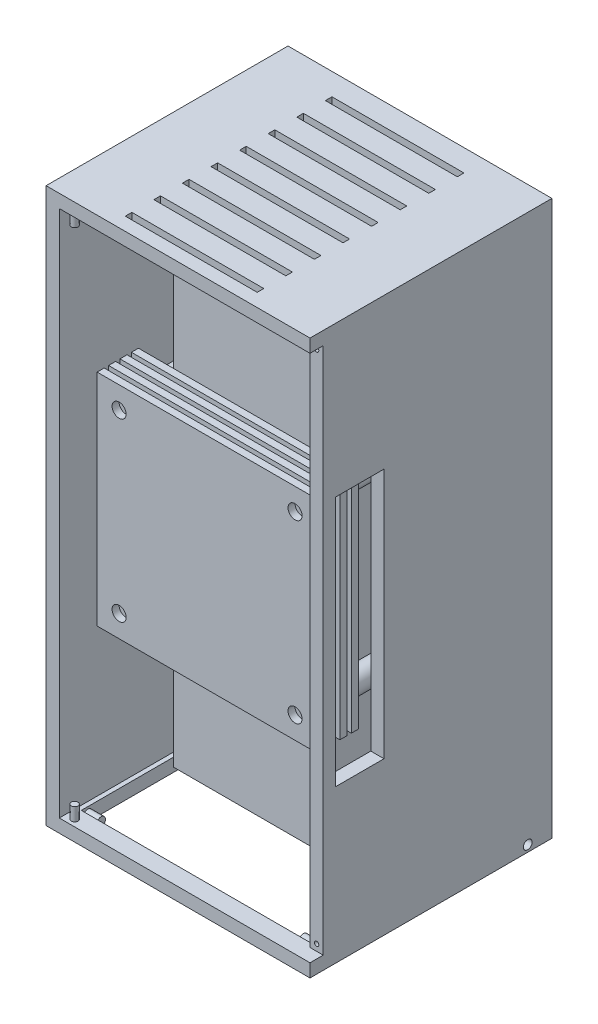
SolidWorks part; units mm, degrees
ref_plane "前视基准面" through (0, 0, 0) normal (0, 0, 1) x (1, 0, 0)
ref_plane "上视基准面" through (0, 0, 0) normal (0, 1, 0) x (1, 0, 0)
ref_plane "右视基准面" through (0, 0, 0) normal (1, 0, 0) x (0, 0, -1)
sketch "草图1" plane through (0, 0, 0) normal (0, 0, 1) x (1, 0, 0)
  line L1 (0, 0) -> (50, 0)
  line L2 (0, 0) -> (0, -50)
  line L3 (0, -50) -> (50, -50)
  line L4 (50, 0) -> (50, -50)
  dimension "D1" = 50
  dimension "D2" = 50
extrude "凸台-拉伸1" add sketch "草图1" along normal blind 1.6
ref_plane "基准面5" through (0, 0, -1) normal (0, 0, -1) x (-1, 0, 0)
sketch "草图4" plane through (0, 0, -1) normal (0, 0, -1) x (-1, 0, 0)
  line L0 (-50, -50) -> (-50, 0) construction
  line L1 (-50, -50) -> (0, -50)
  line L2 (-50, -50) -> (-50, 0)
  line L3 (-50, 0) -> (0, 0)
  line L4 (0, -50) -> (0, 0)
extrude "凸台-拉伸3" add sketch "草图4" along normal blind 1.6 separate body
ref_plane "基准面6" through (0, 0, -3.6) normal (0, 0, -1) x (-1, 0, 0)
sketch "草图5" plane through (0, 0, -3.6) normal (0, 0, -1) x (-1, 0, 0)
  line L1 (0, 0) -> (-50, 0)
  line L2 (0, 0) -> (0, -50)
  line L3 (0, -50) -> (-50, -50)
  line L4 (-50, 0) -> (-50, -50)
extrude "凸台-拉伸4" add sketch "草图5" along normal blind 1.6 separate body
ref_plane "基准面7" through (0, 0, -6.2) normal (0, 0, -1) x (-1, 0, 0)
sketch "草图6" plane through (0, 0, -6.2) normal (0, 0, -1) x (-1, 0, 0)
  line L0 (-50, 0) -> (-50, -50) construction
  line L1 (0, 0) -> (-50, 0)
  line L2 (0, 0) -> (0, -50)
  line L3 (0, -50) -> (-50, -50)
  line L4 (-50, 0) -> (-50, -50)
extrude "凸台-拉伸5" add sketch "草图6" along normal blind 1.6 separate body
ref_plane "基准面8" through (0, 0, -7.8) normal (0, 0, -1) x (-1, 0, 0)
sketch "草图9" plane through (0, 0, -7.8) normal (0, 0, -1) x (-1, 0, 0)
  line L0 (-50, 0) -> (-50, -50) construction
  line L1 (-42, 28.5) -> (-8, 28.5)
  line L2 (-42, 28.5) -> (-42, -78.5)
  line L3 (-42, -78.5) -> (-8, -78.5)
  line L4 (-8, 28.5) -> (-8, -78.5)
  line L5 (0, -50) -> (0, 0) construction
  line L6 (0, 0) -> (-50, 0) construction
  line L7 (-50, -50) -> (0, -50) construction
  dimension "D1" = 8
  dimension "D2" = 8
  dimension "D3" = 28.5
  dimension "D4" = 28.5
extrude "凸台-拉伸6" add sketch "草图9" along normal blind 34 contours L2 L1 L4 L3
fillet "圆角12" radius 3 1 edges at (8, -25, -41.8)
fillet "圆角13" radius 3 1 edges at (42, -25, -41.8)
sketch "草图10" plane through (0, 0, 1.6) normal (0, 0, 1) x (1, 0, 0)
  line L0 (0, 0) -> (0, -50) construction
  line L1 (50, 0) -> (0, 0) construction
  line L2 (50, -50) -> (50, 0) construction
  line L3 (0, -50) -> (50, -50) construction
  circle A0 centre (5, -5) radius 1.6
  circle A1 centre (45, -5) radius 1.6
  circle A2 centre (5, -45) radius 1.6
  circle A3 centre (45, -45) radius 1.6
  dimension "D7" = 3.2
  dimension "D8" = 3.2
  dimension "D9" = 3.2
  dimension "D10" = 3.2
  dimension "D1" = 5
  dimension "D2" = 5
  dimension "D3" = 5
  dimension "D4" = 5
  dimension "D5" = 5
  dimension "D6" = 5
  dimension "D11" = 5
  dimension "D12" = 5
extrude "切除-拉伸1" cut sketch "草图10" against normal blind 10 contours A2 | A0 | A3 | A1
ref_plane "基准面14" through (0, 0, -20.1) normal (0, 0, 1) x (1, 0, 0)
ref_plane "基准面15" through (0, 0, 1.6) normal (0, 0, 1) x (1, 0, 0)
ref_plane "基准面16" through (0, 0, -43.8) normal (0, 0, -1) x (-1, 0, 0)
sketch "草图17" plane through (0, 0, -43.8) normal (0, 0, -1) x (-1, 0, 0)
  line L0 (-39, 28.5) -> (-11, 28.5) construction
  line L1 (-52, 34.5) -> (2, 34.5)
  line L2 (-52, 34.5) -> (-52, -85.5)
  line L3 (-52, -85.5) -> (2, -85.5)
  line L4 (2, 34.5) -> (2, -85.5)
  line L5 (0, -50) -> (0, 0) construction
  dimension "D1" = 120
  dimension "D2" = 6
  dimension "D3" = 54
  dimension "D4" = 2
extrude "凸台-拉伸8" add sketch "草图17" along normal blind 3 separate body
ref_plane "基准面17" through (0, -78.5, 0) normal (0, -1, 0) x (-1, 0, 0)
sketch "草图18" plane through (0, -78.5, 0) normal (0, -1, 0) x (-1, 0, 0)
  line L0 (-8, 38.8) -> (-8, 7.8) construction
  circle A0 centre (-25.0675, 24.3887) radius 15
  dimension "D1" = 30
  dimension "D2" = 17.0675
extrude "凸台-拉伸10" add sketch "草图18" along normal blind 1
ref_plane "基准面18" through (0, -79.5, 0) normal (0, -1, 0) x (-1, 0, 0)
sketch "草图19" plane through (0, -79.5, 0) normal (0, -1, 0) x (-1, 0, 0)
  line L0 (-39, 41.8) -> (-11, 41.8) construction
  circle A0 centre (-25.6075, 24.3) radius 4.5304
  dimension "D1" = 9.0607
  dimension "D2" = 17.5
extrude "凸台-拉伸11" add sketch "草图19" along normal blind 3
sketch "草图22" plane through (0, 0, -7.8) normal (0, 0, -1) x (-1, 0, 0)
  circle A0 centre (-45, -45) radius 2.5
  circle A1 centre (-45, -5) radius 2
  circle A2 centre (-5, -45) radius 2.5
  circle A3 centre (-5, -5) radius 2.5
extrude "凸台-拉伸12" add sketch "草图22" along normal blind 37
ref_plane "基准面19" through (0, 0, -7.8) normal (0, 0, 1) x (1, 0, 0)
sketch "草图23" plane through (0, 0, -7.8) normal (0, 0, 1) x (1, 0, 0)
  circle A0 centre (45, -45) radius 1.6
  circle A1 centre (45, -5) radius 1.6
  circle A2 centre (5, -5) radius 1.6
  circle A3 centre (5, -45) radius 1.6
extrude "切除-拉伸2" cut sketch "草图23" against normal blind 3
ref_plane "基准面21" through (0, 0, -46.8) normal (0, 0, -1) x (-1, 0, 0)
sketch "草图24" plane through (0, 0, -46.8) normal (0, 0, -1) x (-1, 0, 0)
  line L1 (-55, 37.5) -> (5, 37.5)
  line L2 (-55, 37.5) -> (-55, -88.5)
  line L3 (-55, -88.5) -> (5, -88.5)
  line L4 (5, 37.5) -> (5, -88.5)
  line L6 (2, -85.5) -> (2, 34.5) construction
  line L7 (-52, -85.5) -> (2, -85.5) construction
  line L9 (-52, 34.5) -> (2, 34.5)
  line L10 (-52, 34.5) -> (-52, -85.5)
  line L11 (-52, -85.5) -> (2, -85.5)
  line L12 (2, 34.5) -> (2, -85.5)
  dimension "D1" = 60
  dimension "D2" = 126
  dimension "D3" = 3
  dimension "D4" = 3
extrude "凸台-拉伸14" add sketch "草图24" against normal blind 55
ref_plane "基准面24" through (0, 0, 8.2) normal (0, 0, 1) x (1, 0, 0)
sketch "草图27" plane through (0, 0, 8.2) normal (0, 0, 1) x (1, 0, 0)
  line L0 (55, 37.5) -> (55, -88.5) construction
  line L1 (52, 34.5) -> (55, 34.5)
  line L2 (52, 34.5) -> (52, -85.5)
  line L3 (52, -85.5) -> (55, -85.5)
  line L4 (55, 34.5) -> (55, -85.5)
  line L5 (52, -85.5) -> (-2, -85.5) construction
  dimension "D1" = 0
ref_plane "基准面26" through (0, 0, 8.2) normal (0, 0, 1) x (1, 0, 0)
sketch "草图28" plane through (0, 0, 8.2) normal (0, 0, 1) x (1, 0, 0)
  line L0 (55, 37.5) -> (55, -88.5) construction
  line L1 (-2, -85.5) -> (55, -85.5)
  line L2 (-2, -85.5) -> (-2, 34.5)
  line L3 (-2, 34.5) -> (55, 34.5)
  line L4 (55, -85.5) -> (55, 34.5)
  dimension "D1" = 0
ref_plane "基准面31" through (0, -85.5, 0) normal (0, 1, 0) x (1, 0, 0)
sketch "草图29" plane through (0, -85.5, 0) normal (0, 1, 0) x (1, 0, 0)
  line L0 (-2, -8.2) -> (-2, 43.8) construction
  line L1 (-2, -8.2) -> (55, -8.2) construction
  circle A0 centre (0, -6.7) radius 0.75
  dimension "D1" = 1.5
  dimension "D2" = 2
  dimension "D3" = 1.5
ref_plane "基准面32" through (0, 34.5, 0) normal (0, -1, 0) x (-1, 0, 0)
sketch "草图30" plane through (0, 34.5, 0) normal (0, -1, 0) x (-1, 0, 0)
  line L0 (2, -8.2) -> (2, 43.8) construction
  line L1 (2, -8.2) -> (-55, -8.2) construction
  circle A0 centre (0, -6.7) radius 0.75
  dimension "D1" = 1.5
  dimension "D2" = 2
  dimension "D3" = 1.5
ref_plane "基准面33" through (0, 37.5, 0) normal (0, 1, 0) x (1, 0, 0)
sketch "草图31" plane through (0, 37.5, 0) normal (0, 1, 0) x (1, 0, 0)
  line L0 (-5, -8.2) -> (-5, 46.8) construction
  line L1 (10, 41.8) -> (40, 41.8)
  line L2 (10, 41.8) -> (10, 40.3)
  line L3 (10, 40.3) -> (40, 40.3)
  line L4 (40, 41.8) -> (40, 40.3)
  line L5 (10, 35.3) -> (40, 35.3)
  line L6 (10, 35.3) -> (10, 33.8)
  line L7 (10, 33.8) -> (40, 33.8)
  line L8 (40, 35.3) -> (40, 33.8)
  line L9 (10, 28.8) -> (40, 28.8)
  line L10 (10, 28.8) -> (10, 27.3)
  line L11 (10, 27.3) -> (40, 27.3)
  line L12 (40, 28.8) -> (40, 27.3)
  line L13 (10, 22.3) -> (40, 22.3)
  line L14 (10, 22.3) -> (10, 20.8)
  line L15 (10, 20.8) -> (40, 20.8)
  line L16 (40, 22.3) -> (40, 20.8)
  line L17 (10, 15.8) -> (40, 15.8)
  line L18 (10, 15.8) -> (10, 14.3)
  line L19 (10, 14.3) -> (40, 14.3)
  line L20 (40, 15.8) -> (40, 14.3)
  line L21 (10, 9.3) -> (40, 9.3)
  line L22 (10, 9.3) -> (10, 7.8)
  line L23 (10, 7.8) -> (40, 7.8)
  line L24 (40, 9.3) -> (40, 7.8)
  line L25 (10, 2.8) -> (40, 2.8)
  line L26 (10, 2.8) -> (10, 1.3)
  line L27 (10, 1.3) -> (40, 1.3)
  line L28 (40, 2.8) -> (40, 1.3)
  line L29 (10, -3.7) -> (40, -3.7)
  line L30 (10, -3.7) -> (10, -5.2)
  line L31 (10, -5.2) -> (40, -5.2)
  line L32 (40, -3.7) -> (40, -5.2)
  line L33 (-5, 46.8) -> (55, 46.8) construction
  dimension "D1" = 1.5
  dimension "D2" = 30
  dimension "D3" = 15
  dimension "D4" = 5
  dimension "D5" = 0
  dimension "D6" = 0
  dimension "D7" = 0
  dimension "D8" = 0
  dimension "D9" = 0
  dimension "D10" = 0
  dimension "D11" = 0
  dimension "D12" = 5
  dimension "D13" = 1.5
  dimension "D14" = 5
  dimension "D15" = 1.5
  dimension "D16" = 5
  dimension "D17" = 1.5
  dimension "D18" = 5
  dimension "D19" = 1.5
  dimension "D20" = 5
  dimension "D21" = 1.5
  dimension "D22" = 5
  dimension "D23" = 1.5
  dimension "D24" = 5
  dimension "D25" = 1.5
extrude "切除-拉伸4" cut sketch "草图31" against normal blind 4
ref_plane "基准面4" through (0, 0, -1) normal (0, 0, -1) x (-1, 0, 0)
ref_plane "基准面9" through (0, 0, 1.6) normal (0, 0, 1) x (1, 0, 0)
ref_plane "基准面34" through (0, 0, -43.8) normal (0, 0, 1) x (1, 0, 0)
sketch "草图32" plane through (0, 0, -43.8) normal (0, 0, 1) x (1, 0, 0)
  line L0 (-2, 34.5) -> (52, 34.5) construction
  line L1 (-2, -85.5) -> (-2, 34.5) construction
  line L2 (52, 34.5) -> (52, -85.5) construction
  line L3 (52, -85.5) -> (-2, -85.5) construction
  circle A0 centre (2, 30.5) radius 1
  circle A1 centre (48, 30.5) radius 1
  circle A2 centre (2, -81.5) radius 1
  circle A3 centre (48, -81.5) radius 1
  dimension "D1" = 2
  dimension "D4" = 2
  dimension "D7" = 2
  dimension "D8" = 4
  dimension "D11" = 2
  dimension "D2" = 4
  dimension "D3" = 4
  dimension "D5" = 4
  dimension "D6" = 4
  dimension "D9" = 4
  dimension "D10" = 4
  dimension "D12" = 4
extrude "切除-拉伸5" cut sketch "草图32" against normal blind 10
ref_plane "基准面35" through (0, -85.5, 0) normal (0, 1, 0) x (1, 0, 0)
sketch "草图33" plane through (0, -85.5, 0) normal (0, 1, 0) x (1, 0, 0)
  line L0 (-2, -8.2) -> (-2, 43.8) construction
  line L1 (52, -8.2) -> (-2, -8.2)
  line L2 (52, -8.2) -> (52, -5.2)
  line L3 (52, -5.2) -> (-2, -5.2)
  line L4 (-2, -8.2) -> (-2, -5.2)
  dimension "D1" = 3
extrude "凸台-拉伸15" add sketch "草图33" along normal blind 121
ref_plane "基准面36" through (0, -88.5, 0) normal (0, -1, 0) x (-1, 0, 0)
sketch "草图34" plane through (0, -88.5, 0) normal (0, -1, 0) x (-1, 0, 0)
  line L0 (-55, -8.2) -> (5, -8.2) construction
  line L1 (1, -4.2) -> (-51, -4.2)
  line L2 (1, -4.2) -> (1, 42.8)
  line L3 (1, 42.8) -> (-51, 42.8)
  line L4 (-51, -4.2) -> (-51, 42.8)
  line L5 (5, -8.2) -> (5, 46.8) construction
  line L6 (-55, -8.2) -> (-55, 46.8) construction
  line L7 (-55, 46.8) -> (5, 46.8) construction
  dimension "D1" = 4
  dimension "D2" = 4
  dimension "D3" = 4
  dimension "D4" = 4
extrude "切除-拉伸6" cut sketch "草图34" against normal blind 3
ref_plane "基准面39" through (0, -78.5, 0) normal (0, -1, 0) x (-1, 0, 0)
ref_plane "基准面40" through (55, 0, 0) normal (1, 0, 0) x (0, 0, -1)
sketch "草图36" plane through (55, 0, 0) normal (1, 0, 0) x (0, 0, -1)
  line L0 (-8.2, 37.5) -> (-8.2, -88.5) construction
  line L1 (-8.2, -88.5) -> (46.8, -88.5) construction
  circle A0 centre (-2.7, -87) radius 1
  dimension "D1" = 2
  dimension "D2" = 5.5
  dimension "D3" = 1.5
extrude "凸台-拉伸16" add sketch "草图36" against normal blind 58
ref_plane "基准面41" through (48, 0, 0) normal (-1, 0, 0) x (0, 0, 1)
sketch "草图37" plane through (48, 0, 0) normal (-1, 0, 0) x (0, 0, 1)
  line L0 (8.2, 37.5) -> (8.2, -88.5) construction
  line L1 (8.2, -88.5) -> (-46.8, -88.5) construction
  circle A0 centre (2.7, -87) radius 1
  dimension "D2" = 2
  dimension "D1" = 5.5
  dimension "D3" = 1.5
extrude "切除-拉伸8" cut sketch "草图37" along normal blind 46
sketch "草图38" plane through (55, 0, 0) normal (1, 0, 0) x (0, 0, -1)
  line L0 (46.8, 37.5) -> (46.8, -88.5) construction
  line L1 (-8.2, -88.5) -> (46.8, -88.5) construction
  circle A0 centre (41.3, -87) radius 1
  dimension "D1" = 2
  dimension "D2" = 5.5
  dimension "D3" = 1.5
extrude "切除-拉伸9" cut sketch "草图38" against normal blind 100
ref_plane "基准面42" through (55, 0, 0) normal (1, 0, 0) x (0, 0, -1)
sketch "草图39" plane through (55, 0, 0) normal (1, 0, 0) x (0, 0, -1)
  line L1 (-2.4483, 3.2887) -> (8.6243, 3.2887)
  line L2 (-2.4483, 3.2887) -> (-2.4483, -53.7412)
  line L3 (-2.4483, -53.7412) -> (8.6243, -53.7412)
  line L4 (8.6243, 3.2887) -> (8.6243, -53.7412)
extrude "切除-拉伸10" cut sketch "草图39" against normal blind 3
extrude "切除-拉伸11" cut sketch "草图28" against normal blind 3
extrude "凸台-拉伸17" add sketch "草图30" along normal blind 3
extrude "凸台-拉伸18" add sketch "草图29" along normal blind 3
ref_plane "基准面53" through (0, 0, 5.2) normal (0, 0, 1) x (1, 0, 0)
sketch "草图41" plane through (0, 0, 5.2) normal (0, 0, 1) x (1, 0, 0)
  line L0 (55, 34.5) -> (52, 34.5) construction
  line L1 (52, 34.5) -> (52, -85.5) construction
  line L2 (55, -85.5) -> (55, 34.5) construction
  line L3 (52, -85.5) -> (55, -85.5) construction
  circle A0 centre (53.5, 33) radius 0.5
  circle A1 centre (53.5, -84) radius 0.5
  dimension "D1" = 1
  dimension "D4" = 1
  dimension "D2" = 1.5
  dimension "D3" = 1.5
  dimension "D5" = 1.5
  dimension "D6" = 1.5
extrude "切除-拉伸12" cut sketch "草图41" against normal blind 1
ref_plane "基准面54" through (0, 34.5, 0) normal (0, -1, 0) x (-1, 0, 0)
sketch "草图42" plane through (0, 34.5, 0) normal (0, -1, 0) x (-1, 0, 0)
  line L0 (-40, 35.3) -> (-10, 35.3) construction
  line L1 (-14.5, 35.3) -> (-34.5, 35.3)
  line L2 (-14.5, 35.3) -> (-14.5, 40.3)
  line L3 (-14.5, 40.3) -> (-34.5, 40.3)
  line L4 (-34.5, 35.3) -> (-34.5, 40.3)
  line L5 (-10, 40.3) -> (-40, 40.3) construction
  line L6 (2, -8.2) -> (2, 43.8) construction
  line L7 (-40, 15.8) -> (-10, 15.8) construction
  line L8 (-14.5, 15.8) -> (-34.5, 15.8)
  line L9 (-14.5, 15.8) -> (-14.5, 20.8)
  line L10 (-14.5, 20.8) -> (-34.5, 20.8)
  line L11 (-34.5, 15.8) -> (-34.5, 20.8)
  line L12 (-10, 20.8) -> (-40, 20.8) construction
  point P8 (-14.5, 37.8)
  dimension "D1" = 20
  dimension "D2" = 16.5
  dimension "D3" = 20
  dimension "D4" = 0
extrude "凸台-拉伸19" add sketch "草图42" along normal blind 6
